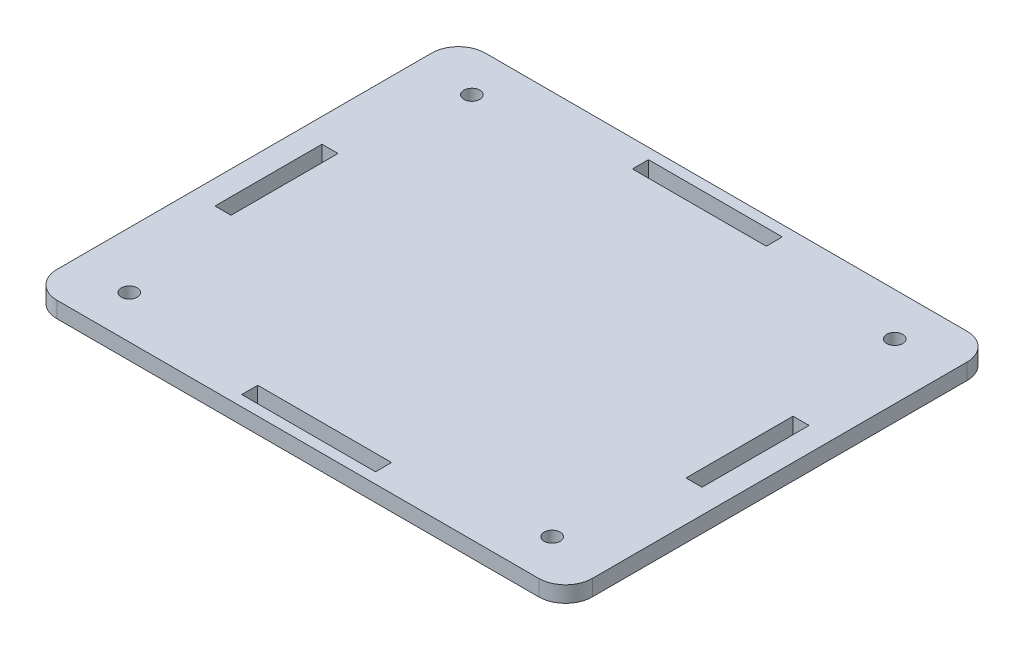
SolidWorks part; units mm, degrees
ref_plane "Front Plane" through (0, 0, 0) normal (0, 0, 1) x (1, 0, 0)
ref_plane "Top Plane" through (0, 0, 0) normal (0, 1, 0) x (1, 0, 0)
ref_plane "Right Plane" through (0, 0, 0) normal (1, 0, 0) x (0, 0, -1)
sketch "Sketch1" plane through (0, 0, 0) normal (0, 1, 0) x (1, 0, 0)
  line L1 (-50, 40) -> (50, 40)
  line L2 (-50, 40) -> (-50, -40)
  line L3 (-50, -40) -> (50, -40)
  line L4 (50, 40) -> (50, -40)
  line L5 (-50, 40) -> (50, -40) construction
  line L6 (-50, -40) -> (50, 40) construction
  point P0 (0, 0)
  dimension "D1" = 100
  dimension "D2" = 80
extrude "Boss-Extrude1" add sketch "Sketch1" along normal blind 3
fillet "Fillet1" radius 5 4 edges at (-50, 1.5, -40) (-50, 1.5, 40) (50, 1.5, 40) (50, 1.5, -40)
sketch "Sketch2" plane through (0, 3, 0) normal (0, 1, 0) x (1, 0, 0)
  line L1 (-39.5, 32) -> (39.5, 32) construction
  line L2 (-39.5, 32) -> (-39.5, -32) construction
  line L3 (-39.5, -32) -> (39.5, -32) construction
  line L4 (39.5, 32) -> (39.5, -32) construction
  line L5 (-39.5, 32) -> (39.5, -32) construction
  line L6 (-39.5, -32) -> (39.5, 32) construction
  circle A0 centre (39.5, -32) radius 1.5
  circle A1 centre (39.5, 32) radius 1.5
  circle A2 centre (-39.5, 32) radius 1.5
  circle A3 centre (-39.5, -32) radius 1.5
  point P0 (0, 0)
  dimension "D1" = 3
  dimension "D2" = 64
  dimension "D3" = 79
extrude "Cut-Extrude1" cut sketch "Sketch2" against normal blind 3
sketch "Sketch3" plane through (0, 3, 0) normal (0, 1, 0) x (1, 0, 0)
  line L0 (-44, 0) -> (0, 0) construction
  line L1 (12.5, -35) -> (-12.5, -35)
  line L2 (12.5, -35) -> (12.5, -38)
  line L3 (12.5, -38) -> (-12.5, -38)
  line L4 (-12.5, -35) -> (-12.5, -38)
  line L5 (12.5, -35) -> (-12.5, -38) construction
  line L6 (12.5, -38) -> (-12.5, -35) construction
  line L7 (12.5, 38) -> (-12.5, 38)
  line L8 (12.5, 38) -> (12.5, 35)
  line L9 (12.5, 35) -> (-12.5, 35)
  line L10 (-12.5, 38) -> (-12.5, 35)
  line L11 (12.5, 38) -> (-12.5, 35) construction
  line L12 (12.5, 35) -> (-12.5, 38) construction
  line L13 (45.5, 10) -> (42.5, 10)
  line L14 (45.5, 10) -> (45.5, -10)
  line L15 (45.5, -10) -> (42.5, -10)
  line L16 (42.5, 10) -> (42.5, -10)
  line L17 (45.5, 10) -> (42.5, -10) construction
  line L18 (45.5, -10) -> (42.5, 10) construction
  line L19 (-42.5, 10) -> (-45.5, 10)
  line L20 (-42.5, 10) -> (-42.5, -10)
  line L21 (-42.5, -10) -> (-45.5, -10)
  line L22 (-45.5, 10) -> (-45.5, -10)
  line L23 (-42.5, 10) -> (-45.5, -10) construction
  line L24 (-42.5, -10) -> (-45.5, 10) construction
  line L25 (0, 0) -> (44, 0) construction
  line L26 (0, -36.5) -> (0, 0) construction
  line L27 (0, 0) -> (0, 36.5) construction
  point P0 (0, -36.5)
  point P5 (0, 36.5)
  point P10 (44, 0)
  point P15 (-44, 0)
  dimension "D1" = 3
  dimension "D2" = 25
  dimension "D3" = 20
  dimension "D4" = 70
  dimension "D5" = 85
extrude "Cut-Extrude2" cut sketch "Sketch3" against normal blind 10
